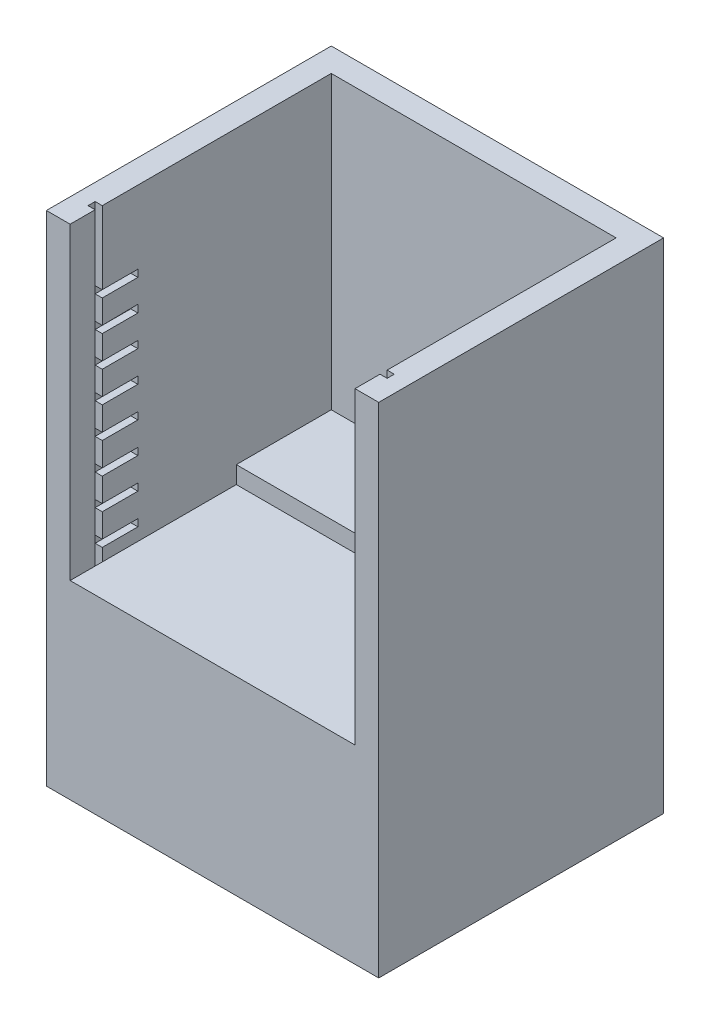
SolidWorks part; units mm, degrees
ref_plane "Front Plane" through (0, 0, 0) normal (0, 0, 1) x (1, 0, 0)
ref_plane "Top Plane" through (0, 0, 0) normal (0, 1, 0) x (1, 0, 0)
ref_plane "Right Plane" through (0, 0, 0) normal (1, 0, 0) x (0, 0, -1)
sketch "Sketch1" plane through (0, 0, 0) normal (0, 1, 0) x (1, 0, 0)
  line L0 (0, 0) -> (140, 0)
  line L1 (140, 0) -> (140, 120)
  line L2 (140, 120) -> (0, 120)
  line L3 (0, 120) -> (0, 0)
  dimension "D1" = 140
  dimension "D2" = 120
extrude "Boss-Extrude1" add sketch "Sketch1" along normal blind 10
sketch "Sketch2" plane through (0, 10, 0) normal (0, 1, 0) x (1, 0, 0)
  line L0 (0, 0) -> (10, 0)
  line L1 (0, 0) -> (140, 0) construction
  line L2 (10, 0) -> (10, 110)
  line L3 (10, 110) -> (130, 110)
  line L4 (130, 110) -> (130, 0)
  line L5 (130, 0) -> (140, 0)
  line L6 (140, 0) -> (140, 120)
  line L7 (140, 120) -> (0, 120)
  line L8 (0, 120) -> (0, 0)
  line L9 (10, 0) -> (10, 10.5363)
  line L10 (10, 10.5363) -> (7, 10.5363)
  line L11 (7, 10.5363) -> (7, 13.5363)
  line L12 (7, 13.5363) -> (10, 13.5363)
  line L13 (70, 120) -> (70, 94.8436) construction
  line L14 (130, 10.5363) -> (133, 10.5363)
  line L15 (133, 10.5363) -> (133, 13.5363)
  line L16 (133, 13.5363) -> (130, 13.5363)
  line M8 (0, 120) -> (0, 0)
  line M9 (0, 0) -> (140, 0)
  line M10 (140, 0) -> (140, 120)
  line M11 (140, 120) -> (0, 120)
  dimension "D1" = 10
  dimension "D2" = 10
  dimension "D3" = 110
  dimension "D4" = 3
  dimension "D5" = 3
extrude "Boss-Extrude2" add sketch "Sketch2" along normal blind 200 contours L13 L7 L2 L10 L11 L12 L3 M8 M9 | L13 L3 L4 L16 L15 L14 M11 M9 M10
sketch "Sketch3" plane through (10, 0, 0) normal (1, 0, 0) x (0, 0, -1)
  line L0 (13.5363, 10) -> (13.5363, 20)
  line L1 (13.5363, 210) -> (13.5363, 10) construction
  line L2 (13.5363, 20) -> (13.5363, 23)
  line L3 (13.5363, 23) -> (13.5363, 33)
  line L4 (13.5363, 33) -> (13.5363, 36)
  line L5 (13.5363, 36) -> (13.5363, 46)
  line L6 (13.5363, 46) -> (13.5363, 49)
  line L7 (13.5363, 49) -> (13.5363, 59)
  line L8 (13.5363, 59) -> (13.5363, 62)
  line L9 (13.5363, 62) -> (13.5363, 72)
  line L10 (13.5363, 72) -> (13.5363, 75)
  line L11 (13.5363, 75) -> (13.5363, 85)
  line L12 (13.5363, 85) -> (13.5363, 85.3191)
  line L13 (13.5363, 85.3191) -> (13.5363, 88.3191)
  line L14 (13.5363, 88.3191) -> (13.5363, 98.3191)
  line L15 (13.5363, 98.3191) -> (13.5363, 92.7222)
  line L16 (13.5363, 92.7222) -> (13.5363, 94.3745)
  line L17 (13.5363, 98.3191) -> (13.5363, 101.3191)
  line L18 (13.5363, 101.3191) -> (13.5363, 111.3191)
  line L19 (13.5363, 111.3191) -> (13.5363, 114.3191)
  line L20 (13.5363, 114.3191) -> (13.5363, 124.3191)
  line L21 (13.5363, 124.3191) -> (13.5363, 127.3191)
  line L22 (13.5363, 127.3191) -> (13.5363, 137.3191)
  line L23 (13.5363, 137.3191) -> (13.5363, 140.3191)
  line L24 (13.5363, 140.3191) -> (13.5363, 150.3191)
  line L25 (13.5363, 150.3191) -> (13.5363, 153.3191)
  line L26 (13.5363, 153.3191) -> (13.5363, 163.3191)
  line L27 (13.5363, 163.3191) -> (13.5363, 166.3191)
  line L28 (13.5363, 166.3191) -> (13.5363, 176.3191)
  line L29 (13.5363, 176.3191) -> (13.5363, 179.3191)
  line L30 (13.5363, 179.3191) -> (13.5363, 189.3191)
  line L31 (13.5363, 20) -> (28.5363, 20)
  line L32 (28.5363, 20) -> (28.5363, 23)
  line L33 (28.5363, 23) -> (13.5363, 23)
  line L34 (13.5363, 33) -> (28.5363, 33)
  line L35 (28.5363, 33) -> (28.5363, 36)
  line L36 (28.5363, 36) -> (13.5363, 36)
  line L37 (13.5363, 46) -> (28.5363, 46)
  line L38 (28.5363, 46) -> (28.5363, 49)
  line L39 (28.5363, 49) -> (13.7571, 49)
  line L40 (13.7571, 49) -> (13.5363, 49)
  line L41 (13.5363, 59) -> (28.5363, 59)
  line L42 (28.5363, 59) -> (28.5363, 62)
  line L43 (28.5363, 62) -> (13.5363, 62)
  line L44 (13.5363, 72) -> (28.534, 71.7375)
  line L45 (28.534, 71.7375) -> (28.534, 75)
  line L46 (28.534, 75) -> (13.5363, 75)
  line L47 (13.5363, 85.3191) -> (28.5363, 85.3191)
  line L48 (28.5363, 85.3191) -> (28.5363, 88.3191)
  line L49 (28.5363, 88.3191) -> (13.5363, 88.3191)
  line L50 (13.5363, 98.3191) -> (28.5363, 98.3191)
  line L51 (28.5363, 98.3191) -> (28.5363, 101.3191)
  line L52 (28.5363, 101.3191) -> (13.5363, 101.3191)
  line L53 (13.5363, 111.3191) -> (28.5363, 111.3191)
  line L54 (28.5363, 111.3191) -> (28.5363, 114.3191)
  line L55 (28.5363, 114.3191) -> (13.5363, 114.3191)
  line L56 (13.5363, 124.3191) -> (28.5363, 124.3191)
  line L57 (28.5363, 124.3191) -> (28.5363, 127.3191)
  line L58 (28.5363, 127.3191) -> (13.5363, 127.3191)
  line L59 (13.5363, 137.3191) -> (28.5363, 137.3191)
  line L60 (28.5363, 137.3191) -> (28.5363, 140.3191)
  line L61 (28.5363, 140.3191) -> (13.5363, 140.3191)
  line L62 (13.5363, 150.3191) -> (28.5363, 150.3191)
  line L63 (28.5363, 150.3191) -> (28.5363, 153.3191)
  line L64 (28.5363, 153.3191) -> (13.5363, 153.3191)
  line L65 (13.5363, 163.3191) -> (28.5363, 163.3191)
  line L66 (28.5363, 163.3191) -> (28.5363, 166.5278)
  line L67 (28.5363, 166.5278) -> (13.5363, 166.3191)
  line L68 (13.5363, 176.3191) -> (28.5363, 176.3191)
  line L69 (28.5363, 176.3191) -> (28.5363, 179.3191)
  line L70 (28.5363, 179.3191) -> (13.5363, 179.3191)
  line M44 (13.5363, 210) -> (13.5363, 10)
  dimension "D1" = 10
  dimension "D2" = 3
  dimension "D3" = 10
  dimension "D4" = 3
  dimension "D5" = 10
  dimension "D6" = 3
  dimension "D7" = 10
  dimension "D8" = 3
  dimension "D9" = 10
  dimension "D10" = 3
  dimension "D11" = 10
  dimension "D12" = 3
  dimension "D13" = 10
  dimension "D14" = 3
  dimension "D15" = 10
  dimension "D16" = 3
  dimension "D17" = 10
  dimension "D18" = 3
  dimension "D19" = 10
  dimension "D20" = 3
  dimension "D21" = 10
  dimension "D22" = 3
  dimension "D23" = 10
  dimension "D24" = 3
  dimension "D25" = 10
  dimension "D26" = 3
  dimension "D27" = 10
  dimension "D28" = 15
  dimension "D29" = 3
  dimension "D30" = 15
  dimension "D31" = 15
  dimension "D32" = 15
  dimension "D33" = 15
  dimension "D34" = 15
  dimension "D35" = 15
  dimension "D36" = 15
  dimension "D37" = 15
  dimension "D38" = 15
  dimension "D39" = 15
  dimension "D40" = 15
  dimension "D41" = 15
extrude "Cut-Extrude1" cut sketch "Sketch3" against normal blind 3 contours L69 L70 L68 M44 | L66 L67 L65 M44 | L63 L64 L62 M44 | L60 L61 L59 M44 | L57 L58 L56 M44 | L54 L55 L53 M44 | L51 L52 L50 M44 | L48 L49 L47 M44 | L45 L46 L44 M44 | L42 L43 L41 M44 | L39 L40 L37 L38 M44 | L35 L36 L34 M44 | L32 L33 L31 M44
sketch "Sketch4" plane through (130, 0, 0) normal (-1, 0, 0) x (0, 0, 1)
  line L0 (-13.5363, 10) -> (-13.5363, 20)
  line L1 (-13.5363, 210) -> (-13.5363, 10) construction
  line L2 (-13.5363, 20) -> (-13.5363, 23)
  line L3 (-13.5363, 23) -> (-13.5363, 33)
  line L4 (-13.5363, 33) -> (-13.5363, 32.0712)
  line L5 (-13.5363, 33) -> (-13.5363, 36)
  line L6 (-13.5363, 36) -> (-13.5363, 46)
  line L7 (-13.5363, 46) -> (-13.5363, 49)
  line L8 (-13.5363, 49) -> (-13.5363, 59)
  line L9 (-13.5363, 59) -> (-13.5363, 62)
  line L10 (-13.5363, 62) -> (-13.5363, 72)
  line L11 (-13.5363, 72) -> (-13.5363, 75)
  line L12 (-13.5363, 75) -> (-13.5363, 85)
  line L13 (-13.5363, 85) -> (-13.5363, 88)
  line L14 (-13.5363, 88) -> (-13.5363, 98)
  line L15 (-13.5363, 98) -> (-13.5363, 101)
  line L16 (-13.5363, 101) -> (-13.5363, 111)
  line L17 (-13.5363, 111) -> (-13.5363, 114)
  line L18 (-13.5363, 114) -> (-13.5363, 124)
  line L19 (-13.5363, 124) -> (-13.5363, 127)
  line L20 (-13.5363, 127) -> (-13.5363, 137)
  line L21 (-13.5363, 137) -> (-13.5363, 140)
  line L22 (-13.5363, 140) -> (-13.5363, 150)
  line L23 (-13.5363, 150) -> (-13.5363, 153)
  line L24 (-13.5363, 153) -> (-13.5363, 163)
  line L25 (-13.5363, 163) -> (-13.5363, 166)
  line L26 (-13.5363, 166) -> (-13.5363, 176)
  line L27 (-13.5363, 176) -> (-13.5363, 179)
  line L28 (-13.5363, 179) -> (-13.5363, 189)
  line L29 (-13.5363, 20) -> (-28.5363, 20)
  line L30 (-28.5363, 20) -> (-28.5363, 23)
  line L31 (-28.5363, 23) -> (-13.5363, 23)
  line L32 (-13.5363, 33) -> (-28.5363, 33)
  line L33 (-28.5363, 33) -> (-28.5363, 36)
  line L34 (-28.5363, 36) -> (-13.5363, 36)
  line L35 (-13.5363, 46) -> (-18.1438, 46)
  line L36 (-18.1438, 46) -> (-28.5363, 46)
  line L37 (-28.5363, 46) -> (-28.5363, 49)
  line L38 (-28.5363, 49) -> (-13.5363, 49)
  line L39 (-13.5363, 59) -> (-28.5363, 59)
  line L40 (-28.5363, 59) -> (-28.5363, 62)
  line L41 (-28.5363, 62) -> (-13.5363, 62)
  line L42 (-13.5363, 72) -> (-28.5363, 72)
  line L43 (-28.5363, 72) -> (-28.5363, 75)
  line L44 (-28.5363, 75) -> (-13.5363, 75)
  line L45 (-13.5363, 85) -> (-28.5363, 85)
  line L46 (-28.5363, 85) -> (-28.5363, 88)
  line L47 (-28.5363, 88) -> (-13.5363, 88)
  line L48 (-13.5363, 98) -> (-28.5363, 98)
  line L49 (-28.5363, 98) -> (-28.5363, 101)
  line L50 (-28.5363, 101) -> (-13.5363, 101)
  line L51 (-13.5363, 111) -> (-28.5363, 111)
  line L52 (-28.5363, 111) -> (-28.5363, 114)
  line L53 (-28.5363, 114) -> (-13.5363, 114)
  line L54 (-13.5363, 124) -> (-28.5363, 124)
  line L55 (-28.5363, 124) -> (-28.5363, 127)
  line L56 (-28.5363, 127) -> (-13.5363, 127)
  line L57 (-13.5363, 137) -> (-28.5363, 137)
  line L58 (-28.5363, 137) -> (-28.5363, 140)
  line L59 (-28.5363, 140) -> (-13.5363, 140)
  line L60 (-13.5363, 150) -> (-28.5363, 150)
  line L61 (-28.5363, 150) -> (-28.5363, 153)
  line L62 (-28.5363, 153) -> (-13.5363, 153)
  line L63 (-13.5363, 163) -> (-28.5363, 163)
  line L64 (-28.5363, 163) -> (-28.5363, 166)
  line L65 (-28.5363, 166) -> (-13.5363, 166)
  line L66 (-13.5363, 176) -> (-28.5363, 176)
  line L67 (-28.5363, 176) -> (-28.5363, 179)
  line L68 (-28.5363, 179) -> (-13.5363, 179)
  line M44 (-13.5363, 10) -> (-13.5363, 210)
  dimension "D1" = 10
  dimension "D3" = 10
  dimension "D4" = 3
  dimension "D5" = 10
  dimension "D6" = 3
  dimension "D7" = 10
  dimension "D8" = 3
  dimension "D9" = 10
  dimension "D10" = 3
  dimension "D11" = 10
  dimension "D12" = 3
  dimension "D13" = 10
  dimension "D14" = 3
  dimension "D15" = 10
  dimension "D16" = 3
  dimension "D17" = 10
  dimension "D18" = 3
  dimension "D19" = 10
  dimension "D20" = 3
  dimension "D21" = 10
  dimension "D22" = 3
  dimension "D23" = 10
  dimension "D24" = 3
  dimension "D25" = 10
  dimension "D26" = 3
  dimension "D27" = 10
  dimension "D28" = 3
  dimension "D29" = 15
  dimension "D30" = 3
  dimension "D31" = 15
  dimension "D32" = 15
  dimension "D33" = 15
  dimension "D34" = 15
  dimension "D35" = 15
  dimension "D36" = 15
  dimension "D37" = 15
  dimension "D38" = 15
  dimension "D39" = 15
  dimension "D40" = 15
  dimension "D41" = 15
  dimension "D42" = 15
extrude "Cut-Extrude2" cut sketch "Sketch4" against normal blind 3 contours L31 L30 L29 M44 | L34 L33 L32 M44 | L38 L37 L36 L35 M44 | L41 L40 L39 M44 | L44 L43 L42 M44 | L47 L46 L45 M44 | L50 L49 L48 M44 | L53 L52 L51 M44 | L56 L55 L54 M44 | L59 L58 L57 M44 | L62 L61 L60 M44 | L65 L64 L63 M44 | L68 L67 L66 M44
sketch "Sketch5" plane through (0, 0, -110) normal (0, 0, 1) x (1, 0, 0)
  line L0 (10, 10) -> (10, 80)
  line L1 (10, 210) -> (10, 10) construction
  line L2 (10, 80) -> (10, 87.284)
  line L3 (10, 87.284) -> (130, 87.284)
  line L4 (130, 210) -> (130, 10) construction
  line L5 (130, 87.284) -> (130, 80)
  line L6 (130, 80) -> (10, 80)
  line M3 (130, 10) -> (130, 210)
  line M5 (10, 210) -> (10, 10)
  dimension "D1" = 70
extrude "Boss-Extrude3" add sketch "Sketch5" along normal blind 40 contours L6 L3 M3 M5
sketch "Sketch6" plane through (0, 0, 0) normal (0, 0, 1) x (1, 0, 0)
  line L0 (10, 10) -> (10, 80)
  line L1 (10, 80) -> (130, 80)
  line L2 (130, 80) -> (130, 10) construction
  line L3 (130, 80) -> (130, 10)
  line L4 (130, 10) -> (10, 10)
  dimension "D1" = 70
extrude "Boss-Extrude4" add sketch "Sketch6" against normal blind 79
